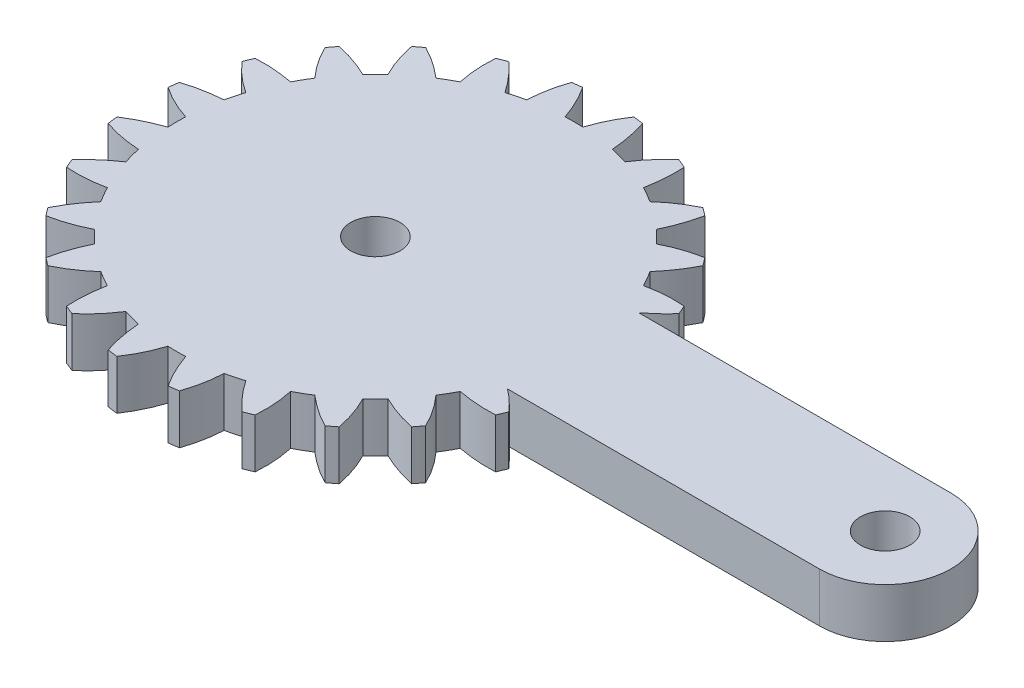
SolidWorks part; units mm, degrees
ref_plane "Front Plane" through (0, 0, 0) normal (0, 0, 1) x (1, 0, 0)
ref_plane "Top Plane" through (0, 0, 0) normal (0, 1, 0) x (1, 0, 0)
ref_plane "Right Plane" through (0, 0, 0) normal (1, 0, 0) x (0, 0, -1)
sketch "Sketch2" plane through (0, 0, 0) normal (0, 1, 0) x (1, 0, 0)
  line L0 (31, 4) -> (12.0129, 4)
  line L1 (31, -4) -> (12.0325, -4)
  line L2 (0, 0) -> (0, 12.09) construction
  line L3 (0, 0) -> (4.397, 16.4099) construction
  line L4 (0, 0) -> (-3.1291, 11.678) construction
  line L5 (-3.6882, 13.7644) -> (-4.4272, 16.5225) construction
  line L6 (0, 14.25) -> (0, 16.5009) construction
  line L7 (0, 0) -> (4.629, 11.1754) construction
  line L8 (4.629, 11.1754) -> (5.4532, 13.1653) construction
  circle A2 centre (31, 0) radius 1.5
  arc A3 (31, -4) -> (31, 4) centre (31, 0) ccw
  arc A12 (6.045, 10.4702) -> (5.5713, 10.7298) centre (0, 0) ccw
  arc A13 (3.6475, 11.5267) -> (3.1291, 11.678) centre (0, 0) ccw
  arc A81 (6.5065, 10.1899) -> (6.045, 10.4702) centre (0, 0) ccw
  arc A82 (8.5489, 8.5489) -> (8.1586, 8.9222) centre (0, 0) ccw
  circle A85 centre (0, 0) radius 1.5
  arc A87 (8.9148, 11.117) -> (8.4309, 11.4884) centre (0, 0) ccw
  arc A89 (8.9221, 8.1587) -> (8.5489, 8.5489) centre (0, 0) ccw
  arc A95 (10.4702, 6.045) -> (10.1898, 6.5066) centre (0, 0) ccw
  arc A97 (11.4884, 8.4309) -> (11.117, 8.9148) centre (0, 0) ccw
  arc A98 (10.7297, 5.5714) -> (10.4702, 6.045) centre (0, 0) ccw
  arc A100 (13.279, 5.1702) -> (13.0455, 5.7338) centre (0, 0) ccw
  arc A115 (10.4702, -6.045) -> (10.7298, -5.5713) centre (0, 0) ccw
  arc A117 (13.0455, -5.7338) -> (13.279, -5.1702) centre (0, 0) ccw
  arc A121 (5.7338, 13.0455) -> (5.1702, 13.279) centre (0, 0) ccw
  arc A161 (10.1899, -6.5065) -> (10.4702, -6.045) centre (0, 0) ccw
  arc A162 (8.5489, -8.5489) -> (8.9222, -8.1586) centre (0, 0) ccw
  arc A163 (11.117, -8.9148) -> (11.4884, -8.4309) centre (0, 0) ccw
  arc A164 (8.1587, -8.9221) -> (8.5489, -8.5489) centre (0, 0) ccw
  arc A165 (6.045, -10.4702) -> (6.5066, -10.1898) centre (0, 0) ccw
  arc A166 (8.4309, -11.4884) -> (8.9148, -11.117) centre (0, 0) ccw
  arc A167 (5.5714, -10.7297) -> (6.045, -10.4702) centre (0, 0) ccw
  arc A168 (3.1291, -11.678) -> (3.6476, -11.5266) centre (0, 0) ccw
  arc A169 (5.1702, -13.279) -> (5.7338, -13.0455) centre (0, 0) ccw
  arc A170 (2.6045, -11.8061) -> (3.1291, -11.678) centre (0, 0) ccw
  arc A171 (0, -12.09) -> (0.54, -12.0779) centre (0, 0) ccw
  arc A172 (1.5572, -14.1647) -> (2.162, -14.085) centre (0, 0) ccw
  arc A173 (-0.5399, -12.0779) -> (0, -12.09) centre (0, 0) ccw
  arc A174 (-3.1291, -11.678) -> (-2.6044, -11.8062) centre (0, 0) ccw
  arc A175 (-2.162, -14.085) -> (-1.5572, -14.1647) centre (0, 0) ccw
  arc A176 (-3.6475, -11.5267) -> (-3.1291, -11.678) centre (0, 0) ccw
  arc A177 (-6.045, -10.4702) -> (-5.5713, -10.7298) centre (0, 0) ccw
  arc A178 (-5.7338, -13.0455) -> (-5.1702, -13.279) centre (0, 0) ccw
  arc A179 (-6.5065, -10.1899) -> (-6.045, -10.4702) centre (0, 0) ccw
  arc A180 (-8.5489, -8.5489) -> (-8.1586, -8.9222) centre (0, 0) ccw
  arc A181 (-8.9148, -11.117) -> (-8.4309, -11.4884) centre (0, 0) ccw
  arc A182 (-8.9221, -8.1587) -> (-8.5489, -8.5489) centre (0, 0) ccw
  arc A183 (-10.4702, -6.045) -> (-10.1898, -6.5066) centre (0, 0) ccw
  arc A184 (-11.4884, -8.4309) -> (-11.117, -8.9148) centre (0, 0) ccw
  arc A185 (-10.7297, -5.5714) -> (-10.4702, -6.045) centre (0, 0) ccw
  arc A186 (-11.678, -3.1291) -> (-11.5266, -3.6476) centre (0, 0) ccw
  arc A187 (-13.279, -5.1702) -> (-13.0455, -5.7338) centre (0, 0) ccw
  arc A188 (-11.8061, -2.6045) -> (-11.678, -3.1291) centre (0, 0) ccw
  arc A189 (-12.09, 0) -> (-12.0779, -0.54) centre (0, 0) ccw
  arc A190 (-14.1647, -1.5572) -> (-14.085, -2.162) centre (0, 0) ccw
  arc A191 (-12.0779, 0.5399) -> (-12.09, 0) centre (0, 0) ccw
  arc A192 (-11.678, 3.1291) -> (-11.8062, 2.6044) centre (0, 0) ccw
  arc A193 (-14.085, 2.162) -> (-14.1647, 1.5572) centre (0, 0) ccw
  arc A194 (-11.5267, 3.6475) -> (-11.678, 3.1291) centre (0, 0) ccw
  arc A195 (-10.4702, 6.045) -> (-10.7298, 5.5713) centre (0, 0) ccw
  arc A196 (-13.0455, 5.7338) -> (-13.279, 5.1702) centre (0, 0) ccw
  arc A197 (-10.1899, 6.5065) -> (-10.4702, 6.045) centre (0, 0) ccw
  arc A198 (-8.5489, 8.5489) -> (-8.9222, 8.1586) centre (0, 0) ccw
  arc A199 (-11.117, 8.9148) -> (-11.4884, 8.4309) centre (0, 0) ccw
  arc A200 (-8.1587, 8.9221) -> (-8.5489, 8.5489) centre (0, 0) ccw
  arc A201 (-6.045, 10.4702) -> (-6.5066, 10.1898) centre (0, 0) ccw
  arc A202 (-8.4309, 11.4884) -> (-8.9148, 11.117) centre (0, 0) ccw
  arc A203 (-5.5714, 10.7297) -> (-6.045, 10.4702) centre (0, 0) ccw
  arc A204 (-3.1291, 11.678) -> (-3.6476, 11.5266) centre (0, 0) ccw
  arc A205 (-5.1702, 13.279) -> (-5.7338, 13.0455) centre (0, 0) ccw
  arc A206 (-2.6045, 11.8061) -> (-3.1291, 11.678) centre (0, 0) ccw
  arc A207 (0, 12.09) -> (-0.54, 12.0779) centre (0, 0) ccw
  arc A208 (-1.5572, 14.1647) -> (-2.162, 14.085) centre (0, 0) ccw
  arc A209 (0.5399, 12.0779) -> (0, 12.09) centre (0, 0) ccw
  arc A210 (3.1291, 11.678) -> (2.6044, 11.8062) centre (0, 0) ccw
  arc A211 (2.162, 14.085) -> (1.5572, 14.1647) centre (0, 0) ccw
  arc A212 (12.09, 0) -> (12.0779, 0.54) centre (0, 0) ccw [skipped]
  arc A213 (14.1647, 1.5572) -> (14.085, 2.162) centre (0, 0) ccw [skipped]
  arc A214 (12.0779, -0.5399) -> (12.09, 0) centre (0, 0) ccw [skipped]
  arc A215 (11.678, -3.1291) -> (11.8062, -2.6044) centre (0, 0) ccw [skipped]
  arc A216 (14.085, -2.162) -> (14.1647, -1.5572) centre (0, 0) ccw [skipped]
  arc A217 (11.5267, -3.6475) -> (11.678, -3.1291) centre (0, 0) ccw [skipped]
  arc A218 (11.8061, 2.6045) -> (11.678, 3.1291) centre (0, 0) ccw [skipped]
  arc A219 (11.678, 3.1291) -> (11.5266, 3.6476) centre (0, 0) ccw [skipped]
  spline S0 degree 3 poles (8.9148, 11.117) (8.7604, 10.3435) (8.4826, 9.6001) (8.1586, 8.9222) knots 0.154713 0.154713 0.154713 0.154713 1 1 1 1
  spline S1 degree 3 poles (6.5065, 10.1899) (7.0658, 10.6979) (7.7126, 11.1471) (8.4309, 11.4884) knots 0 0 0 0 0.845227 0.845227 0.845227 0.845227
  spline S2 degree 3 poles (11.4884, 8.4309) (11.139, 7.7237) (10.6783, 7.0775) (10.1898, 6.5066) knots 0.154713 0.154713 0.154713 0.154713 1 1 1 1
  spline S3 degree 3 poles (8.9221, 8.1587) (9.5939, 8.5047) (10.3348, 8.7711) (11.117, 8.9148) knots 0 0 0 0 0.845227 0.845227 0.845227 0.845227
  spline S4 degree 3 poles (3.6475, 11.5267) (4.0562, 12.1622) (4.5647, 12.7634) (5.1702, 13.279) knots 0 0 0 0 0.845227 0.845227 0.845227 0.845227
  spline S5 degree 3 poles (5.7338, 13.0455) (5.7848, 12.2584) (5.7089, 11.4685) (5.5713, 10.7298) knots 0.154713 0.154713 0.154713 0.154713 1 1 1 1
  spline S6 degree 3 poles (13.279, 5.1702) (12.8955, 4.7335) (12.4622, 4.3445) (12.0129, 4) knots 0.154713 0.154713 0.154713 0.154713 0.77749 0.77749 0.77749 0.77749
  spline S7 degree 3 poles (10.7297, 5.5714) (11.4681, 5.7318) (12.2528, 5.7974) (13.0455, 5.7338) knots 0 0 0 0 0.845227 0.845227 0.845227 0.845227
  spline S12 degree 3 poles (13.0455, -5.7338) (12.2584, -5.7848) (11.4685, -5.7089) (10.7298, -5.5713) knots 0.154713 0.154713 0.154713 0.154713 1 1 1 1
  spline S13 degree 3 poles (12.0325, -4) (12.4803, -4.3376) (12.9025, -4.728) (13.279, -5.1702) knots 0.228019 0.228019 0.228019 0.228019 0.845227 0.845227 0.845227 0.845227
  spline S14 degree 3 poles (11.117, -8.9148) (10.3435, -8.7604) (9.6001, -8.4826) (8.9222, -8.1586) knots 0.154713 0.154713 0.154713 0.154713 1 1 1 1
  spline S15 degree 3 poles (10.1899, -6.5065) (10.6979, -7.0658) (11.1471, -7.7126) (11.4884, -8.4309) knots 0 0 0 0 0.845227 0.845227 0.845227 0.845227
  spline S16 degree 3 poles (8.4309, -11.4884) (7.7237, -11.139) (7.0775, -10.6783) (6.5066, -10.1898) knots 0.154713 0.154713 0.154713 0.154713 1 1 1 1
  spline S17 degree 3 poles (8.1587, -8.9221) (8.5047, -9.5939) (8.7711, -10.3348) (8.9148, -11.117) knots 0 0 0 0 0.845227 0.845227 0.845227 0.845227
  spline S18 degree 3 poles (5.1702, -13.279) (4.5775, -12.7584) (4.0726, -12.1462) (3.6476, -11.5266) knots 0.154713 0.154713 0.154713 0.154713 1 1 1 1
  spline S19 degree 3 poles (5.5714, -10.7297) (5.7318, -11.4681) (5.7974, -12.2528) (5.7338, -13.0455) knots 0 0 0 0 0.845227 0.845227 0.845227 0.845227
  spline S20 degree 3 poles (1.5572, -14.1647) (1.1194, -13.5085) (0.7902, -12.7864) (0.54, -12.0779) knots 0.154713 0.154713 0.154713 0.154713 1 1 1 1
  spline S21 degree 3 poles (2.6045, -11.8061) (2.5683, -12.5609) (2.4286, -13.3358) (2.162, -14.085) knots 0 0 0 0 0.845227 0.845227 0.845227 0.845227
  spline S22 degree 3 poles (-2.162, -14.085) (-2.415, -13.3379) (-2.5461, -12.5553) (-2.6044, -11.8062) knots 0.154713 0.154713 0.154713 0.154713 1 1 1 1
  spline S23 degree 3 poles (-0.5399, -12.0779) (-0.7702, -12.7976) (-1.1057, -13.5099) (-1.5572, -14.1647) knots 0 0 0 0 0.845227 0.845227 0.845227 0.845227
  spline S24 degree 3 poles (-5.7338, -13.0455) (-5.7848, -12.2584) (-5.7089, -11.4685) (-5.5713, -10.7298) knots 0.154713 0.154713 0.154713 0.154713 1 1 1 1
  spline S25 degree 3 poles (-3.6475, -11.5267) (-4.0562, -12.1622) (-4.5647, -12.7634) (-5.1702, -13.279) knots 0 0 0 0 0.845227 0.845227 0.845227 0.845227
  spline S26 degree 3 poles (-8.9148, -11.117) (-8.7604, -10.3435) (-8.4826, -9.6001) (-8.1586, -8.9222) knots 0.154713 0.154713 0.154713 0.154713 1 1 1 1
  spline S27 degree 3 poles (-6.5065, -10.1899) (-7.0658, -10.6979) (-7.7126, -11.1471) (-8.4309, -11.4884) knots 0 0 0 0 0.845227 0.845227 0.845227 0.845227
  spline S28 degree 3 poles (-11.4884, -8.4309) (-11.139, -7.7237) (-10.6783, -7.0775) (-10.1898, -6.5066) knots 0.154713 0.154713 0.154713 0.154713 1 1 1 1
  spline S29 degree 3 poles (-8.9221, -8.1587) (-9.5939, -8.5047) (-10.3348, -8.7711) (-11.117, -8.9148) knots 0 0 0 0 0.845227 0.845227 0.845227 0.845227
  spline S30 degree 3 poles (-13.279, -5.1702) (-12.7584, -4.5775) (-12.1462, -4.0726) (-11.5266, -3.6476) knots 0.154713 0.154713 0.154713 0.154713 1 1 1 1
  spline S31 degree 3 poles (-10.7297, -5.5714) (-11.4681, -5.7318) (-12.2528, -5.7974) (-13.0455, -5.7338) knots 0 0 0 0 0.845227 0.845227 0.845227 0.845227
  spline S32 degree 3 poles (-14.1647, -1.5572) (-13.5085, -1.1194) (-12.7864, -0.7902) (-12.0779, -0.54) knots 0.154713 0.154713 0.154713 0.154713 1 1 1 1
  spline S33 degree 3 poles (-11.8061, -2.6045) (-12.5609, -2.5683) (-13.3358, -2.4286) (-14.085, -2.162) knots 0 0 0 0 0.845227 0.845227 0.845227 0.845227
  spline S34 degree 3 poles (-14.085, 2.162) (-13.3379, 2.415) (-12.5553, 2.5461) (-11.8062, 2.6044) knots 0.154713 0.154713 0.154713 0.154713 1 1 1 1
  spline S35 degree 3 poles (-12.0779, 0.5399) (-12.7976, 0.7702) (-13.5099, 1.1057) (-14.1647, 1.5572) knots 0 0 0 0 0.845227 0.845227 0.845227 0.845227
  spline S36 degree 3 poles (-13.0455, 5.7338) (-12.2584, 5.7848) (-11.4685, 5.7089) (-10.7298, 5.5713) knots 0.154713 0.154713 0.154713 0.154713 1 1 1 1
  spline S37 degree 3 poles (-11.5267, 3.6475) (-12.1622, 4.0562) (-12.7634, 4.5647) (-13.279, 5.1702) knots 0 0 0 0 0.845227 0.845227 0.845227 0.845227
  spline S38 degree 3 poles (-11.117, 8.9148) (-10.3435, 8.7604) (-9.6001, 8.4826) (-8.9222, 8.1586) knots 0.154713 0.154713 0.154713 0.154713 1 1 1 1
  spline S39 degree 3 poles (-10.1899, 6.5065) (-10.6979, 7.0658) (-11.1471, 7.7126) (-11.4884, 8.4309) knots 0 0 0 0 0.845227 0.845227 0.845227 0.845227
  spline S40 degree 3 poles (-8.4309, 11.4884) (-7.7237, 11.139) (-7.0775, 10.6783) (-6.5066, 10.1898) knots 0.154713 0.154713 0.154713 0.154713 1 1 1 1
  spline S41 degree 3 poles (-8.1587, 8.9221) (-8.5047, 9.5939) (-8.7711, 10.3348) (-8.9148, 11.117) knots 0 0 0 0 0.845227 0.845227 0.845227 0.845227
  spline S42 degree 3 poles (-5.1702, 13.279) (-4.5775, 12.7584) (-4.0726, 12.1462) (-3.6476, 11.5266) knots 0.154713 0.154713 0.154713 0.154713 1 1 1 1
  spline S43 degree 3 poles (-5.5714, 10.7297) (-5.7318, 11.4681) (-5.7974, 12.2528) (-5.7338, 13.0455) knots 0 0 0 0 0.845227 0.845227 0.845227 0.845227
  spline S44 degree 3 poles (-1.5572, 14.1647) (-1.1194, 13.5085) (-0.7902, 12.7864) (-0.54, 12.0779) knots 0.154713 0.154713 0.154713 0.154713 1 1 1 1
  spline S45 degree 3 poles (-2.6045, 11.8061) (-2.5683, 12.5609) (-2.4286, 13.3358) (-2.162, 14.085) knots 0 0 0 0 0.845227 0.845227 0.845227 0.845227
  spline S46 degree 3 poles (2.162, 14.085) (2.415, 13.3379) (2.5461, 12.5553) (2.6044, 11.8062) knots 0.154713 0.154713 0.154713 0.154713 1 1 1 1
  spline S47 degree 3 poles (0.5399, 12.0779) (0.7702, 12.7976) (1.1057, 13.5099) (1.5572, 14.1647) knots 0 0 0 0 0.845227 0.845227 0.845227 0.845227
  point P11 (0, 12.09)
  point P15 (-3.1291, 11.678)
  point P167 (0, 0)
  point P177 (0, 0)
  dimension "D1" = 3
  dimension "D2" = 8
  dimension "D7" = 24
  dimension "D8" = 3.1561
  dimension "D6" = 24
  dimension "D15" = 0.61
  dimension "D3" = 31
  dimension "D4" = 15
  dimension "D5" = 15
  dimension "D16" = 7.5
  dimension "D17" = 180
extrude "Boss-Extrude1" add sketch "Sketch2" along normal blind 3
scale "Ölçek1" bodies to scale 102 scale about centroid uniform scaling yes scale factor 2
